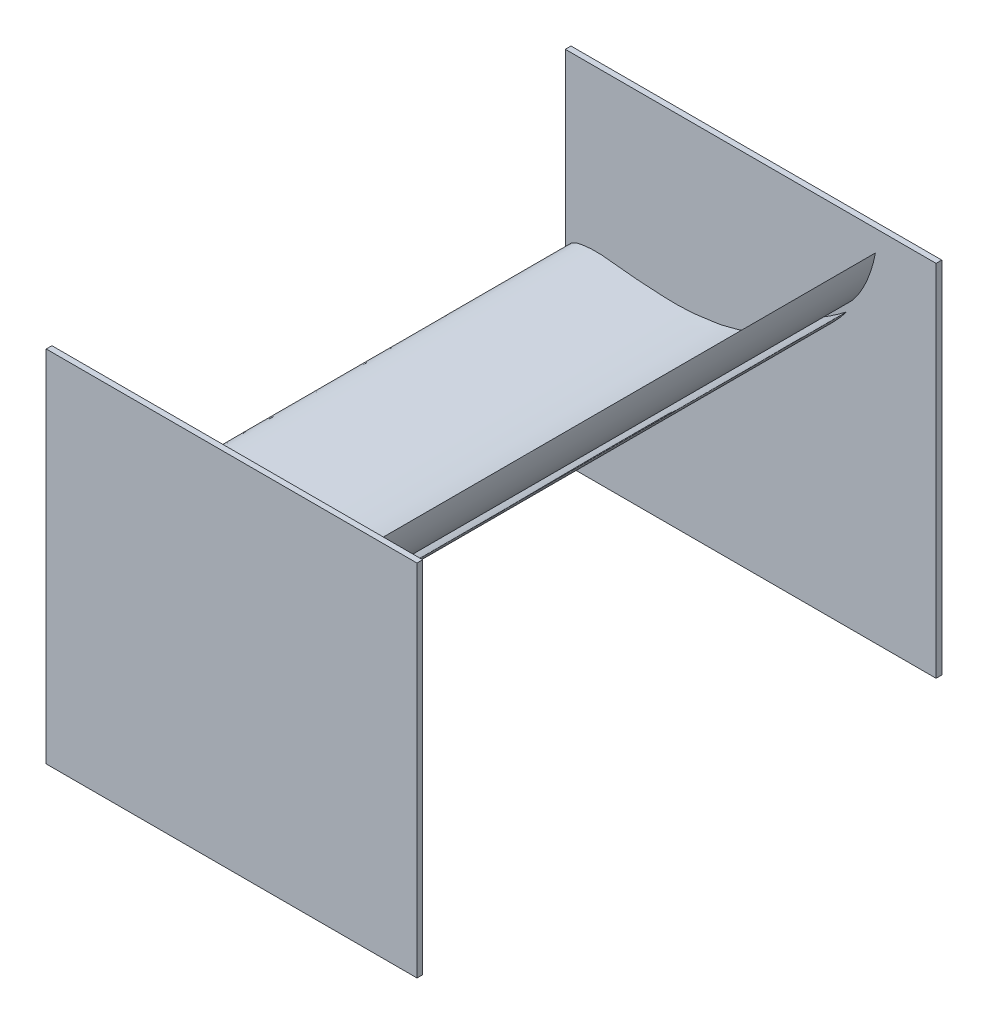
SolidWorks part; units mm, degrees
ref_plane "Front Plane" through (0, 0, 0) normal (0, 0, 1) x (1, 0, 0)
ref_plane "Top Plane" through (0, 0, 0) normal (0, 1, 0) x (1, 0, 0)
ref_plane "Right Plane" through (0, 0, 0) normal (1, 0, 0) x (0, 0, -1)
sketch "Sketch1" plane through (0, 0, 0) normal (0, 0, 1) x (1, 0, 0)
  line L0 (46.9575, 64.3181) -> (1074.8558, 208.7798) construction
sketch "Sketch2" plane through (0, 0, 0) normal (0, 0, 1) x (1, 0, 0)
  line L0 (0, 0) -> (400, 0) construction
  line L1 (0, 0) -> (399.6225, 66.8739) construction
  line L2 (0, 66.8739) -> (0, -66.8739) construction
  line L3 (10.0115, 66.8739) -> (10.0115, -116.1581) construction
  line L4 (20.0229, 66.8739) -> (20.0229, -116.1581) construction
  line L5 (30.0344, 66.8739) -> (30.0344, -116.1581) construction
  line L6 (40.0459, 66.8739) -> (40.0459, -116.1581) construction
  line L7 (50.0573, 66.8739) -> (50.0573, -116.1581) construction
  line L8 (60.0688, 66.8739) -> (60.0688, -116.1581) construction
  line L9 (70.0803, 66.8739) -> (70.0803, -116.1581) construction
  line L10 (80.0918, 66.8739) -> (80.0918, -116.1581) construction
  line L11 (90.1032, 66.8739) -> (90.1032, -116.1581) construction
  line L12 (100.1147, 66.8739) -> (100.1147, -116.1581) construction
  line L13 (110.1262, 66.8739) -> (110.1262, -116.1581) construction
  line L14 (120.1376, 66.8739) -> (120.1376, -116.1581) construction
  line L15 (130.1491, 66.8739) -> (130.1491, -116.1581) construction
  line L16 (140.1606, 66.8739) -> (140.1606, -116.1581) construction
  line L17 (150.172, 66.8739) -> (150.172, -116.1581) construction
  line L18 (160.1835, 66.8739) -> (160.1835, -116.1581) construction
  line L19 (170.195, 66.8739) -> (170.195, -116.1581) construction
  line L20 (180.2064, 66.8739) -> (180.2064, -116.1581) construction
  line L21 (190.2179, 66.8739) -> (190.2179, -116.1581) construction
  line L22 (200.2294, 66.8739) -> (200.2294, -116.1581) construction
  line L23 (210.2408, 66.8739) -> (210.2408, -116.1581) construction
  line L24 (220.2523, 66.8739) -> (220.2523, -116.1581) construction
  line L25 (230.2638, 66.8739) -> (230.2638, -116.1581) construction
  line L26 (240.2753, 66.8739) -> (240.2753, -116.1581) construction
  line L27 (250.2867, 66.8739) -> (250.2867, -116.1581) construction
  line L28 (260.2982, 66.8739) -> (260.2982, -116.1581) construction
  line L29 (270.3097, 66.8739) -> (270.3097, -116.1581) construction
  line L30 (280.3211, 66.8739) -> (280.3211, -116.1581) construction
  line L31 (290.3326, 66.8739) -> (290.3326, -116.1581) construction
  line L32 (300.3441, 66.8739) -> (300.3441, -116.1581) construction
  line L33 (310.3555, 66.8739) -> (310.3555, -116.1581) construction
  line L34 (320.367, 66.8739) -> (320.367, -116.1581) construction
  line L35 (330.3785, 66.8739) -> (330.3785, -116.1581) construction
  line L36 (340.3899, 66.8739) -> (340.3899, -116.1581) construction
  line L37 (350.4014, 66.8739) -> (350.4014, -116.1581) construction
  line L38 (360.4129, 66.8739) -> (360.4129, -116.1581) construction
  line L39 (370.4243, 66.8739) -> (370.4243, -116.1581) construction
  line L40 (380.4358, 66.8739) -> (380.4358, -116.1581) construction
  line L41 (390.4473, 66.8739) -> (390.4473, -116.1581) construction
  line L42 (400.4588, 66.8739) -> (400.4588, -116.1581) construction
  line L43 (836.1007, 66.8739) -> (-36.8556, 66.8739) construction
  line L44 (389.6225, 76.8739) -> (409.6225, 76.8739) construction
  line L45 (399.6225, 90.7703) -> (399.6225, 62.9774) construction
  line L46 (539.2399, 261.0337) -> (478.7399, 156.2446) construction
  line L47 (488.7399, 146.2766) -> (482.6971, 142.1346) construction
  line L48 (389.6225, 76.8739) -> (488.7399, 146.2766) construction
  line L51 (488.7399, 194.8045) -> (488.7399, 123.7678) construction
  line L52 (478.7399, 201.6203) -> (478.7399, 116.9521) construction
  line L53 (478.7399, 156.2446) -> (614.5057, 156.2446) construction
  line L54 (389.6225, 83.3039) -> (389.6225, -27.4023) construction
  line L55 (478.7399, 146.2446) -> (614.5057, 146.2446) construction
  spline S0 degree 3 poles (8.4176, 12.2629) (-5.1, -0.6947) (8.0175, -15.4806) (19.5512, -21.724) (30.0167, -25.3022) (39.86, -28.8642) (50.0404, -30.6629) (60.0706, -32.2577) (70.0139, -34.2177) (80.101, -34.56) (90.0931, -35.3652) (100.112, -35.9529) (110.1282, -35.5072) (120.1532, -35.21) (130.1503, -34.2298) (140.19, -33.4102) (150.1782, -31.9134) (160.1704, -30.3713) (170.2408, -29.1636) (180.2083, -27.151) (190.2638, -25.3061) (200.2392, -22.8725) (210.2446, -20.4291) (220.2329, -17.8951) (230.3811, -15.7054) (240.3519, -12.3911) (253.5512, -7.3696) (266.9476, -2.8065) (280.4369, 1.6366) (290.3614, 5.8195) (300.4407, 10.0322) (310.3048, 14.8841) (323.8214, 20.8842) (337.3023, 27.2498) (350.2747, 34.8502) (364.0374, 41.2007) (378.0734, 50.4319) (389.2687, 56.9917) (404.9331, 70.6704) (388.8931, 60.8973) (380.9617, 56.8333) (370.3166, 52.1732) (360.4136, 47.7491) (350.4697, 43.0754) (340.4967, 38.8332) (330.4052, 35.261) (320.3498, 31.8494) (310.3583, 28.3259) (300.4869, 24.6622) (290.3218, 22.3006) (280.2904, 19.7619) (270.4267, 16.765) (260.336, 15.0613) (250.2769, 13.9588) (240.2662, 12.5783) (230.2787, 11.0679) (220.2867, 9.6964) (210.2433, 9.2404) (200.2287, 9.0345) (190.217, 8.2792) (180.2125, 9.1624) (170.1842, 8.7285) (160.1865, 9.5822) (150.1678, 9.9892) (140.1635, 10.7007) (130.146, 11.2145) (120.1214, 11.8409) (110.1328, 12.9697) (100.1148, 13.8501) (90.0938, 14.7159) (80.0796, 15.8427) (56.9177, 18.8475) (32.3828, 18.9634) (8.4176, 12.2629) (-5.1, -0.6947) (8.0175, -15.4806) knots -0.089629 -0.030705 -0.018228 0 0.022024 0.035622 0.048197 0.060585 0.072602 0.084545 0.096479 0.108284 0.12009 0.131879 0.143661 0.155449 0.167269 0.1791 0.190991 0.202897 0.214788 0.226766 0.238768 0.250864 0.262992 0.27512 0.287235 0.299601 0.31215 0.337082 0.349542 0.362249 0.375072 0.388091 0.40103 0.427261 0.440709 0.453892 0.481344 0.495528 0.510184 0.522428 0.535733 0.548643 0.561554 0.574511 0.587287 0.599816 0.612271 0.624763 0.637218 0.649381 0.661544 0.67375 0.685718 0.697586 0.709472 0.721375 0.733243 0.74504 0.756824 0.768611 0.780398 0.792175 0.803972 0.815766 0.827567 0.839363 0.851169 0.863006 0.874833 0.88666 0.89851 0.910371 0.969295 0.981772 1 1.022024 1.035622 1.048197 only from (0, 0) to (0, 0)
  spline S1 degree 3 poles (488.4807, 145.9571) (488.8121, 146.3498) (488.4243, 146.015) (488.0622, 145.7851) (487.2625, 145.1263) (486.2197, 144.3713) (484.8735, 143.3367) (483.2507, 142.1161) (481.3449, 140.7026) (479.1839, 139.1083) (476.7613, 137.3643) (474.1237, 135.4494) (471.2368, 133.4393) (468.1657, 131.2913) (464.8962, 129.0676) (461.4575, 126.7695) (457.874, 124.4106) (454.1513, 122.027) (450.3296, 119.6083) (446.4184, 117.1921) (442.4423, 114.7926) (438.4319, 112.4153) (434.4211, 110.0589) (430.4193, 107.7484) (426.4691, 105.4752) (422.5724, 103.27) (418.7829, 101.1054) (415.1038, 99.0189) (411.5811, 96.98) (408.2231, 95.0247) (405.0701, 93.1172) (402.1178, 91.3128) (399.4157, 89.5543) (396.9653, 87.8935) (394.7924, 86.3186) (392.9158, 84.83) (391.3498, 83.4309) (390.0835, 82.1509) (389.1526, 80.9646) (388.5665, 79.872) (388.3105, 78.8689) (388.4525, 77.9475) (389.0134, 77.2045) (389.9156, 76.685) (391.1282, 76.3842) (392.6501, 76.2546) (394.4851, 76.3138) (396.6232, 76.5794) (399.0459, 77.0357) (401.7358, 77.7205) (404.6757, 78.5968) (407.8392, 79.7049) (411.2008, 81.0269) (414.7209, 82.591) (418.3956, 84.3418) (422.1799, 86.3091) (426.0457, 88.48) (429.9704, 90.8288) (433.915, 93.3645) (437.8712, 96.0402) (441.7934, 98.8661) (445.6685, 101.7972) (449.4657, 104.8272) (453.1679, 107.924) (456.7615, 111.054) (460.2029, 114.2195) (463.5191, 117.343) (466.6501, 120.455) (469.6136, 123.4898) (472.3702, 126.4509) (474.954, 129.2656) (477.2978, 131.9605) (479.4562, 134.4635) (481.3811, 136.7846) (483.0779, 138.8974) (484.5577, 140.7696) (485.8099, 142.3825) (486.8479, 143.7389) (487.6258, 144.7686) (488.2511, 145.5957) (488.4807, 145.9571) (488.8121, 146.3498) (488.4243, 146.015) knots -0.00692 -0.003098 -0.00077 0 0.000781 0.003074 0.006931 0.012248 0.01903 0.027226 0.036785 0.04761 0.059602 0.072764 0.086897 0.102004 0.117939 0.134556 0.151858 0.169651 0.187838 0.206374 0.225065 0.243814 0.262569 0.281137 0.299514 0.317506 0.335105 0.352118 0.368488 0.384167 0.398955 0.412906 0.425872 0.437811 0.448585 0.458213 0.466669 0.473884 0.479894 0.484779 0.488743 0.492167 0.495628 0.499576 0.504487 0.510576 0.517943 0.526574 0.536524 0.54764 0.560015 0.573491 0.588031 0.603544 0.619912 0.637089 0.654944 0.673346 0.692212 0.711461 0.73091 0.750475 0.770022 0.789461 0.808651 0.827458 0.84582 0.863559 0.880666 0.896945 0.912322 0.926718 0.939993 0.952161 0.96306 0.972662 0.980906 0.987733 0.99308 0.996902 0.99923 1 1.000781 1.003074 1.006931 only from (488.7399, 146.2766) to (488.7399, 146.2766)
  spline S2 degree 3 poles (539.1474, 260.6327) (539.2727, 261.1311) (539.0712, 260.66) (538.847, 260.2944) (538.4178, 259.3511) (537.8126, 258.2147) (537.0576, 256.6938) (536.1358, 254.8842) (535.0445, 252.777) (533.8032, 250.3953) (532.3928, 247.7642) (530.8643, 244.8851) (529.1535, 241.8109) (527.3379, 238.5318) (525.3773, 235.0977) (523.2973, 231.5223) (521.114, 227.8287) (518.8164, 224.0518) (516.4453, 220.1998) (513.9926, 216.3108) (511.4744, 212.4083) (508.9156, 208.5106) (506.3472, 204.6315) (503.7668, 200.7977) (501.2162, 197.0199) (498.684, 193.3269) (496.2302, 189.7174) (493.8413, 186.2265) (491.572, 182.8471) (489.4139, 179.6152) (487.4191, 176.5163) (485.5592, 173.5982) (483.904, 170.8313) (482.432, 168.2626) (481.1716, 165.8931) (480.1395, 163.7313) (479.3471, 161.7863) (478.7717, 160.08) (478.4564, 158.6052) (478.4098, 157.3661) (478.6205, 156.3524) (479.1528, 155.587) (479.9832, 155.1657) (481.022, 155.0953) (482.2436, 155.3578) (483.6679, 155.9099) (485.2905, 156.7692) (487.0948, 157.9471) (489.0711, 159.4214) (491.187, 161.2183) (493.4434, 163.297) (495.7989, 165.6824) (498.2384, 168.3469) (500.714, 171.2985) (503.2464, 174.4858) (505.7822, 177.9159) (508.3018, 181.5646) (510.7961, 185.3989) (513.2262, 189.41) (515.6053, 193.552) (517.8878, 197.8139) (520.0818, 202.1497) (522.1624, 206.5401) (524.1282, 210.9489) (525.9819, 215.3396) (527.6833, 219.6955) (529.2906, 223.9586) (530.7366, 228.1301) (532.0659, 232.1586) (533.2418, 236.03) (534.3267, 239.6939) (535.2487, 243.1448) (536.0884, 246.3418) (536.7982, 249.2728) (537.3945, 251.9164) (537.9016, 254.2486) (538.3181, 256.2478) (538.6549, 257.9225) (538.9014, 259.1894) (539.0999, 260.2071) (539.1474, 260.6327) (539.2727, 261.1311) (539.0712, 260.66) knots -0.00692 -0.003098 -0.00077 0 0.000781 0.003074 0.006931 0.012248 0.01903 0.027226 0.036785 0.04761 0.059602 0.072764 0.086897 0.102004 0.117939 0.134556 0.151858 0.169651 0.187838 0.206374 0.225065 0.243814 0.262569 0.281137 0.299514 0.317506 0.335105 0.352118 0.368488 0.384167 0.398955 0.412906 0.425872 0.437811 0.448585 0.458213 0.466669 0.473884 0.479894 0.484779 0.488743 0.492167 0.495628 0.499576 0.504487 0.510576 0.517943 0.526574 0.536524 0.54764 0.560015 0.573491 0.588031 0.603544 0.619912 0.637089 0.654944 0.673346 0.692212 0.711461 0.73091 0.750475 0.770022 0.789461 0.808651 0.827458 0.84582 0.863559 0.880666 0.896945 0.912322 0.926718 0.939993 0.952161 0.96306 0.972662 0.980906 0.987733 0.99308 0.996902 0.99923 1 1.000781 1.003074 1.006931 only from (539.2399, 261.0337) to (539.2399, 261.0337)
  point P7 (0, 0)
  point P94 (399.6225, 76.8739)
  point P100 (399.6225, 76.8739)
  point P108 (399.6225, 66.8739)
  point P112 (389.6225, 76.8739)
  point P126 (488.7399, 146.2766)
  point P130 (488.7399, 156.2766)
  point P136 (488.7399, 159.2862)
  point P142 (478.7399, 159.2862)
  dimension "D1" = 9.5
  dimension "D3" = 405.1793
  dimension "D4" = 400
  dimension "D5" = 121
  dimension "D6" = 10
  dimension "D7" = 35
  dimension "D8" = 10
  dimension "D9" = 60
  dimension "D10" = 10
  dimension "D11" = 121
  dimension "D12" = 10
  dimension "D13" = 79.3707
  dimension "D2" = 41
extrude "Boss-Extrude1" add sketch "Sketch2" along normal blind 900
ref_plane "Plane1" through (0, 0, 900) normal (0, 0, 1) x (1, 0, 0)
sketch "Sketch3" plane through (0, 0, 900) normal (0, 0, 1) x (1, 0, 0)
  line L0 (535.5966, 298.3743) -> (535.5966, -331.6257) construction
  line L1 (-4.4034, 298.3743) -> (645.5966, 298.3743)
  line L2 (-4.4034, 298.3743) -> (-4.4034, -331.6257)
  line L3 (-4.4034, -331.6257) -> (645.5966, -331.6257)
  line L4 (645.5966, 298.3743) -> (645.5966, -331.6257)
  dimension "D1" = 110
  dimension "D2" = 650
  dimension "D3" = 630
extrude "Boss-Extrude2" add sketch "Sketch3" along normal blind 10
sketch "Sketch5" plane through (0, 0, 0) normal (0, 0, 1) x (1, 0, 0)
  line L0 (535.5966, 298.3743) -> (535.5966, -331.6257) construction
  line L1 (-4.4034, 298.3743) -> (645.5966, 298.3743)
  line L2 (-4.4034, 298.3743) -> (-4.4034, -331.6257)
  line L3 (-4.4034, -331.6257) -> (645.5966, -331.6257)
  line L4 (645.5966, 298.3743) -> (645.5966, -331.6257)
  dimension "D1" = 110
  dimension "D2" = 650
  dimension "D3" = 630
extrude "Boss-Extrude3" add sketch "Sketch5" against normal blind 10 contours L2 L3 L4 L1
ref_plane "Plane2" through (0, 0, 450) normal (0, 0, 1) x (1, 0, 0)
